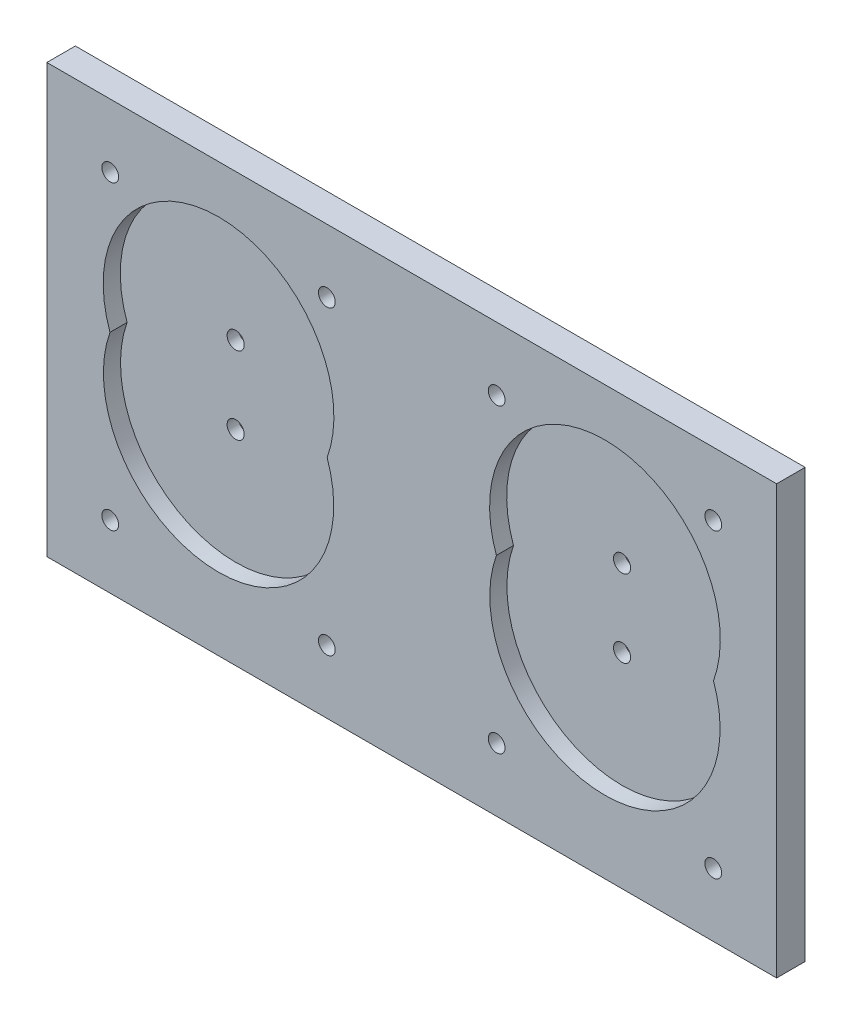
SolidWorks part; units mm, degrees
ref_plane "Front Plane" through (0, 0, 0) normal (0, 0, 1) x (1, 0, 0)
ref_plane "Top Plane" through (0, 0, 0) normal (0, 1, 0) x (1, 0, 0)
ref_plane "Right Plane" through (0, 0, 0) normal (1, 0, 0) x (0, 0, -1)
sketch "Sketch1" plane through (0, 0, 0) normal (0, 0, 1) x (1, 0, 0)
  line L0 (-27, 37) -> (18, 37) construction
  line L1 (-34.62, -30.465) -> (93.4045, -30.465)
  line L2 (-34.62, -30.465) -> (-34.62, 44.62)
  line L3 (-34.62, 44.62) -> (93.4045, 44.62)
  line L4 (93.4045, -30.465) -> (93.4045, 44.62)
  line L6 (18, -22.845) -> (-27, -22.845) construction
  line L7 (29.3923, 47.4436) -> (29.3923, -48.0943) construction
  line L8 (-1.522, 35.265) -> (0.428, 34.861) construction
  line L9 (-22.495, 23.506) -> (-23.167, 21.631) construction
  line L10 (14.167, 21.631) -> (14.645, 19.697) construction
  line L11 (-20.427, -8.82) -> (-22.01, -6.152) construction
  line L12 (13.01, -6.152) -> (11.427, -8.82) construction
  line L13 (-7.593, -16.823) -> (-4.5, -17.07) construction
  circle A0 centre (-4.5, 15.9942) radius 19.4742
  circle A1 centre (63.2846, 15.9942) radius 19.4742
  circle A2 centre (-4.5, 2.4297) radius 19.4378
  circle A3 centre (63.2845, 2.4297) radius 19.4378
  circle A4 centre (-4.5, 15.9942) radius 20.2362
  circle A5 centre (-4.5, 2.4297) radius 20.1998
  circle A6 centre (63.2845, 2.4297) radius 20.1998
  circle A7 centre (63.2846, 15.9942) radius 20.2362
  dimension "D5" = 0.762
  dimension "D6" = 0.762
  dimension "D1" = 7.62
  dimension "D2" = 7.62
  dimension "D3" = 7.62
  dimension "D4" = 7.62
extrude "Boss-Extrude1" add sketch "Sketch1" along normal blind 5 contours L3 L7 L1 L4 A7 A6 | L7 L3 L2 L1 A5 A4
sketch "Sketch7" plane through (0, 0, 5) normal (0, 0, 1) x (1, 0, 0)
  circle A0 centre (-23.5006, 33.4996) radius 1.4732
  circle A1 centre (14.4994, 33.5003) radius 1.4732
  circle A2 centre (-23.4996, -19.3454) radius 1.4732
  circle A3 centre (14.5004, -19.3447) radius 1.4732
  circle A4 centre (44.2848, -19.3453) radius 1.4732
  circle A5 centre (44.2842, 33.4997) radius 1.4732
  circle A6 centre (82.2842, 33.5002) radius 1.4732
  circle A7 centre (82.2848, -19.3448) radius 1.4732
  circle A8 centre (-23.5006, 33.4996) radius 1.4732 construction
extrude "Cut-Extrude1" cut sketch "Sketch7" against normal blind 10
sketch "Sketch8" plane through (0, 0, 0) normal (0, 0, -1) x (-1, 0, 0)
  arc A0 (-44.2381, 9.1578) -> (-82.331, 9.1577) centre (-63.2846, 15.9942) ccw
  arc A1 (-44.2381, 9.1578) -> (-82.331, 9.1577) centre (-63.2846, 15.9942) ccw construction
  arc A2 (-82.331, 9.1577) -> (-44.2381, 9.1578) centre (-63.2845, 2.4297) ccw
  arc A3 (-82.331, 9.1577) -> (-44.2381, 9.1578) centre (-63.2845, 2.4297) ccw construction
  circle A4 centre (-63.2845, 2.4297) radius 1.5
  circle A5 centre (-63.2846, 15.9942) radius 1.5
  arc A6 (23.5465, 9.1577) -> (-14.5464, 9.1578) centre (4.5, 15.9942) ccw
  arc A7 (-14.5464, 9.1578) -> (23.5465, 9.1577) centre (4.5, 2.4297) ccw
  arc A8 (-14.5464, 9.1578) -> (23.5465, 9.1577) centre (4.5, 2.4297) ccw construction
  arc A9 (23.5465, 9.1577) -> (-14.5464, 9.1578) centre (4.5, 15.9942) ccw construction
  circle A10 centre (4.5, 15.9942) radius 1.5
  circle A11 centre (4.5, 2.4297) radius 1.5
  dimension "D1" = 3
extrude "Boss-Extrude2" add sketch "Sketch8" against normal blind 2
